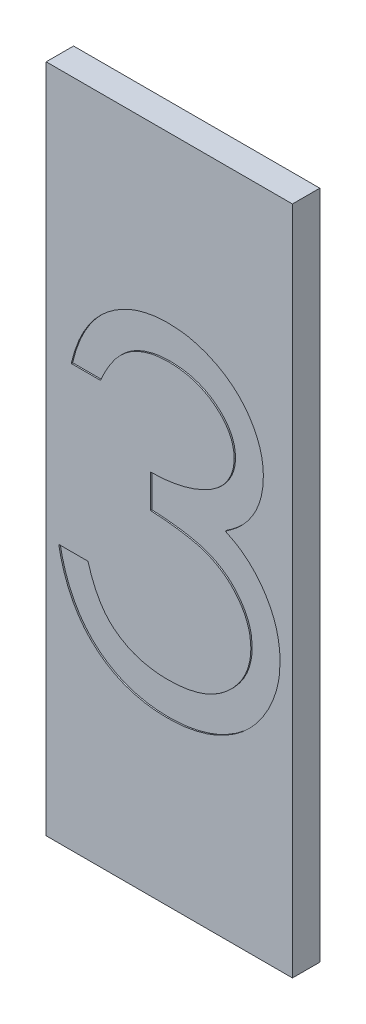
SolidWorks part; units mm, degrees
ref_plane "正面" through (0, 0, 0) normal (0, 0, 1) x (1, 0, 0)
ref_plane "平面" through (0, 0, 0) normal (0, 1, 0) x (1, 0, 0)
ref_plane "右側面" through (0, 0, 0) normal (1, 0, 0) x (0, 0, -1)
sketch "ｽｹｯﾁ1" plane through (0, 0, 0) normal (0, 0, 1) x (1, 0, 0)
  line L0 (18, 0) -> (0, 0)
  line L1 (18, 49) -> (0, 49)
  line L2 (0, 0) -> (0, 49)
  line L4 (18, 0) -> (18, 49)
extrude "ﾎﾞｽ - 押し出し1" add sketch "ｽｹｯﾁ1" along normal blind 2
sketch "ｽｹｯﾁ2" plane through (0, 0, 2) normal (0, 0, 1) x (1, 0, 0)
  text T0 "3" font "Century Gothic" height in points 90
extrude "ｶｯﾄ - 押し出し1" cut sketch "ｽｹｯﾁ2" against normal blind 0.1
